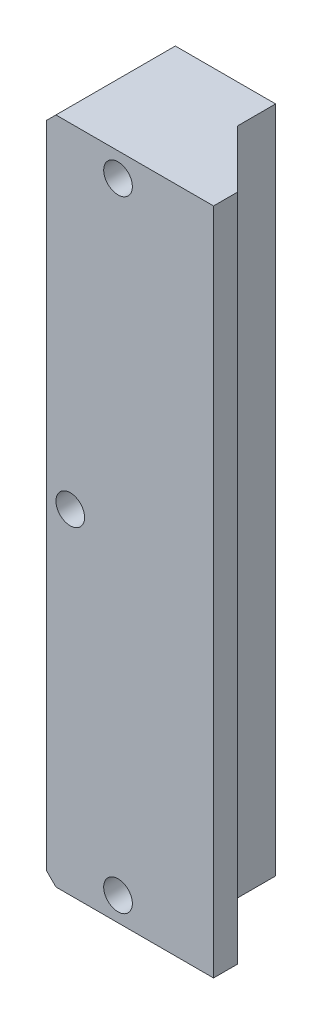
SolidWorks part; units mm, degrees
material "6061 Alloy"
ref_plane "Front Plane" through (0, 0, 0) normal (0, 0, 1) x (1, 0, 0)
ref_plane "Top Plane" through (0, 0, 0) normal (0, 1, 0) x (1, 0, 0)
ref_plane "Right Plane" through (0, 0, 0) normal (1, 0, 0) x (0, 0, -1)
sketch "Sketch1" plane through (0, 0, 0) normal (0, 0, 1) x (1, 0, 0)
  line L0 (17.5, 0) -> (-17.5, 0) construction
  line L1 (17.5, 70) -> (-17.5, 70)
  line L2 (17.5, 70) -> (17.5, -70)
  line L3 (17.5, -70) -> (-17.5, -70)
  line L4 (-17.5, 70) -> (-17.5, -70)
  point P4 (0, 0)
  dimension "D3" = 35
  dimension "D4" = 140
extrude "Boss-Extrude1" add sketch "Sketch1" along normal blind 25
sketch "Sketch2" plane through (0, -70, 0) normal (0, -1, 0) x (1, 0, 0)
  line L0 (5.5, 0) -> (5.5, 8)
  line L1 (-17.5, 0) -> (17.5, 0) construction
  line L2 (5.5, 8) -> (17.5, 20)
  line L3 (17.5, 25) -> (17.5, 0) construction
  dimension "D1" = 12
  dimension "D2" = 135
  dimension "D3" = 20
extrude "Cut-Extrude1" cut sketch "Sketch2" against normal through all and the other way through all flip side to cut
sketch "Sketch3" plane through (0, 0, 25) normal (0, 0, 1) x (1, 0, 0)
  line L0 (-17.5, 0) -> (17.5, 0) construction
  line L1 (-17.5, 70) -> (-17.5, -70) construction
  line L2 (17.5, -70) -> (17.5, 70) construction
  point P0 (-12.5, 0)
  point P1 (-2.5, 65)
  point P2 (-2.5, -65)
  dimension "D1" = 20
  dimension "D2" = 65
  dimension "D3" = 10
hole_wizard "CBORE for M3 Hexagon socket head cap screws1" positions "Sketch4" profile "Sketch5" counterbore size "M3" standard "GB" end condition through all
sketch "Sketch4" plane through (0, 0, 25) normal (0, 0, 1) x (1, 0, 0)
  point P0 (-2.5, 65)
  point P2 (-12.5, 0)
  point P4 (-2.5, -65)
sketch "Sketch5" plane through (-2.5, 65, 25) normal (1, 0, 0) x (0, -1, 0)
  line L0 (0, 0) -> (0, 25)
  line L1 (0, 25) -> (1.6, 25)
  line L3 (1.6, 25) -> (1.6, 18.4)
  line L4 (1.6, 18.4) -> (3, 18.4)
  line L5 (3, 18.4) -> (3, 0)
  line L7 (3, 0) -> (0, 0)
  line L11 (0, -6.35) -> (0, 107.95) construction
  dimension "Thru Hole Dia." = 3.2
  dimension "Thru Hole Depth" = 25
  dimension "C'Bore Dia." = 6
  dimension "C'Bore Depth" = 18.4
fillet "Fillet1" [suppressed] radius 2
chamfer "Chamfer1" distance 2 angle 45 2 edges at (-17.5, -70, 12.5) (-17.5, 70, 12.5)
